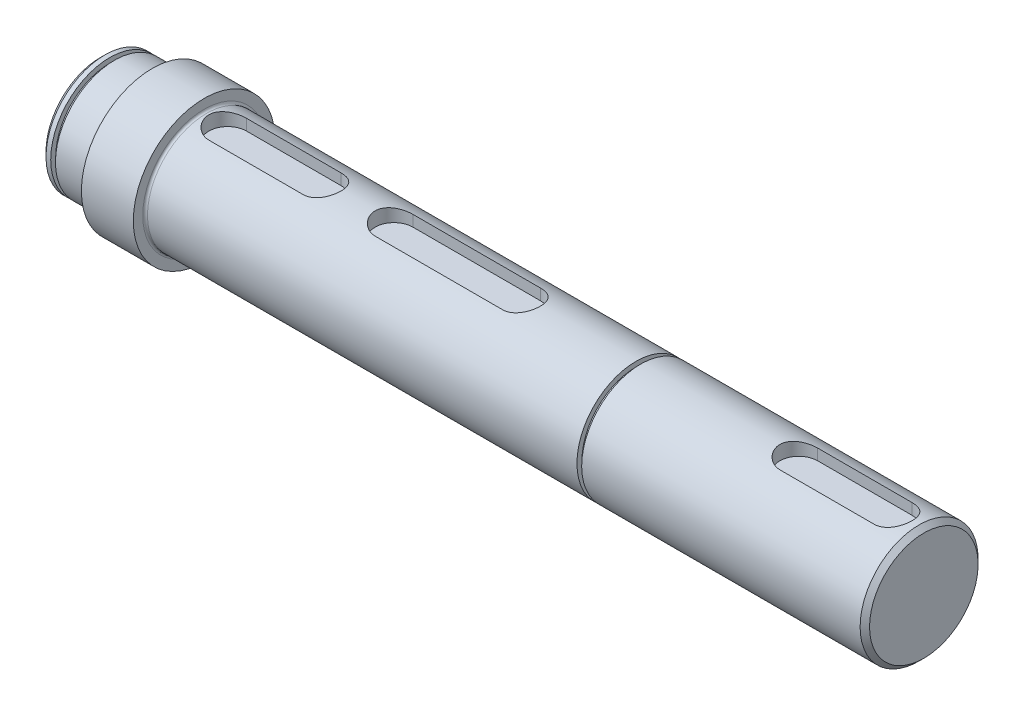
SolidWorks part; units mm, degrees
material "1.0050 (E295)"
ref_plane "Front Plane" through (0, 0, 0) normal (0, 0, 1) x (1, 0, 0)
ref_plane "Top Plane" through (0, 0, 0) normal (0, 1, 0) x (1, 0, 0)
ref_plane "Right Plane" through (0, 0, 0) normal (1, 0, 0) x (0, 0, -1)
sketch "Sketch1" plane through (0, 0, 0) normal (0, 0, 1) x (1, 0, 0)
  line L0 (0, 0) -> (349, 0)
  line L1 (0, 0) -> (0, 23)
  line L2 (349, 23) -> (349, 0)
  line L3 (2, 25) -> (4, 25)
  line L4 (0, 23) -> (2, 25)
  line L5 (4, 25) -> (4, 22.9)
  line L6 (4, 22.9) -> (6, 22.9)
  line L7 (6, 22.9) -> (6, 25)
  line L8 (22, 25) -> (22, 30)
  line L9 (22, 30) -> (44, 30)
  line L10 (44, 30) -> (44, 25)
  line L11 (6, 25) -> (22, 25)
  line L12 (44, 25) -> (227, 25)
  line L13 (229, 25) -> (347, 25)
  line L14 (347, 25) -> (349, 23)
  line L16 (227, 25) -> (227, 22.9)
  line L17 (227, 22.9) -> (229, 22.9)
  line L18 (229, 22.9) -> (229, 25)
  point P4 (0, 25)
  point P5 (349, 25)
  point P13 (104, 25)
  point P16 (114, 25)
  point P17 (189, 25)
  dimension "D2" = 22.9
  dimension "D3" = 2
  dimension "D5" = 6
  dimension "D6" = 16
  dimension "D7" = 98
  dimension "D8" = 60
  dimension "D9" = 5
  dimension "D10" = 10
  dimension "D11" = 38
  dimension "D12" = 75
  dimension "D13" = 22.9
  dimension "D14" = 25
  dimension "D15" = 2
  dimension "D16" = 120
revolve "Revolve1" add sketch "Sketch1" angle 360 about L0
ref_plane "Plane1" through (0, 25, 0) normal (0, 1, 0) x (1, 0, 0)
sketch "Sketch2" plane through (0, 25, 0) normal (0, 1, 0) x (1, 0, 0)
  line L0 (0, 0) -> (349, 0) construction
  line L1 (349, -23) -> (349, 23) construction
  line L2 (54, 0) -> (94, 0) construction
  line L3 (54, 8) -> (94, 8)
  line L4 (54, -8) -> (94, -8)
  line L6 (44, -30) -> (44, 30) construction
  arc A0 (54, 8) -> (54, -8) centre (54, 0) ccw
  arc A1 (94, -8) -> (94, 8) centre (94, 0) ccw
  point P7 (74, 0)
  point P12 (46, 0)
  dimension "D1" = 56
  dimension "D2" = 2
  dimension "D3" = 16
extrude "Cut-Extrude1" cut sketch "Sketch2" against normal blind 6
sketch "Sketch3" plane through (0, 25, 0) normal (0, 1, 0) x (1, 0, 0)
  line L0 (0, 0) -> (349, 0) construction
  line L1 (349, -23) -> (349, 23) construction
  line L2 (44, -25) -> (44, 25) construction
  line L3 (124.5, 0) -> (178.5, 0) construction
  line L4 (124.5, 8) -> (178.5, 8)
  line L5 (124.5, -8) -> (178.5, -8)
  arc A0 (124.5, 8) -> (124.5, -8) centre (124.5, 0) ccw
  arc A1 (178.5, -8) -> (178.5, 8) centre (178.5, 0) ccw
  point P5 (114, 0)
  point P10 (151.5, 0)
  dimension "D2" = 2.5
  dimension "D4" = 70
  dimension "D1" = 70
  dimension "D3" = 16
extrude "Cut-Extrude2" cut sketch "Sketch3" against normal blind 6
fillet "Fillet1" radius 1 1 edges at (44, 0, 25)
ref_plane "Plane2" through (0, 25, 0) normal (0, 1, 0) x (1, 0, 0)
sketch "Sketch4" plane through (0, 25, 0) normal (0, 1, 0) x (1, 0, 0)
  line L0 (349, 0) -> (229, 0) construction
  line L1 (349, -23) -> (349, 23) construction
  line L2 (229, 22.9) -> (229, -22.9) construction
  line L3 (296, 0) -> (336, 0) construction
  line L4 (296, 8) -> (336, 8)
  line L5 (296, -8) -> (336, -8)
  arc A0 (296, 8) -> (296, -8) centre (296, 0) ccw
  arc A1 (336, -8) -> (336, 8) centre (336, 0) ccw
  point P8 (316, 0)
  point P13 (288, 0)
  point P14 (344, 0)
  dimension "D1" = 56
  dimension "D2" = 16
  dimension "D3" = 5
extrude "Cut-Extrude3" cut sketch "Sketch4" against normal blind 6
